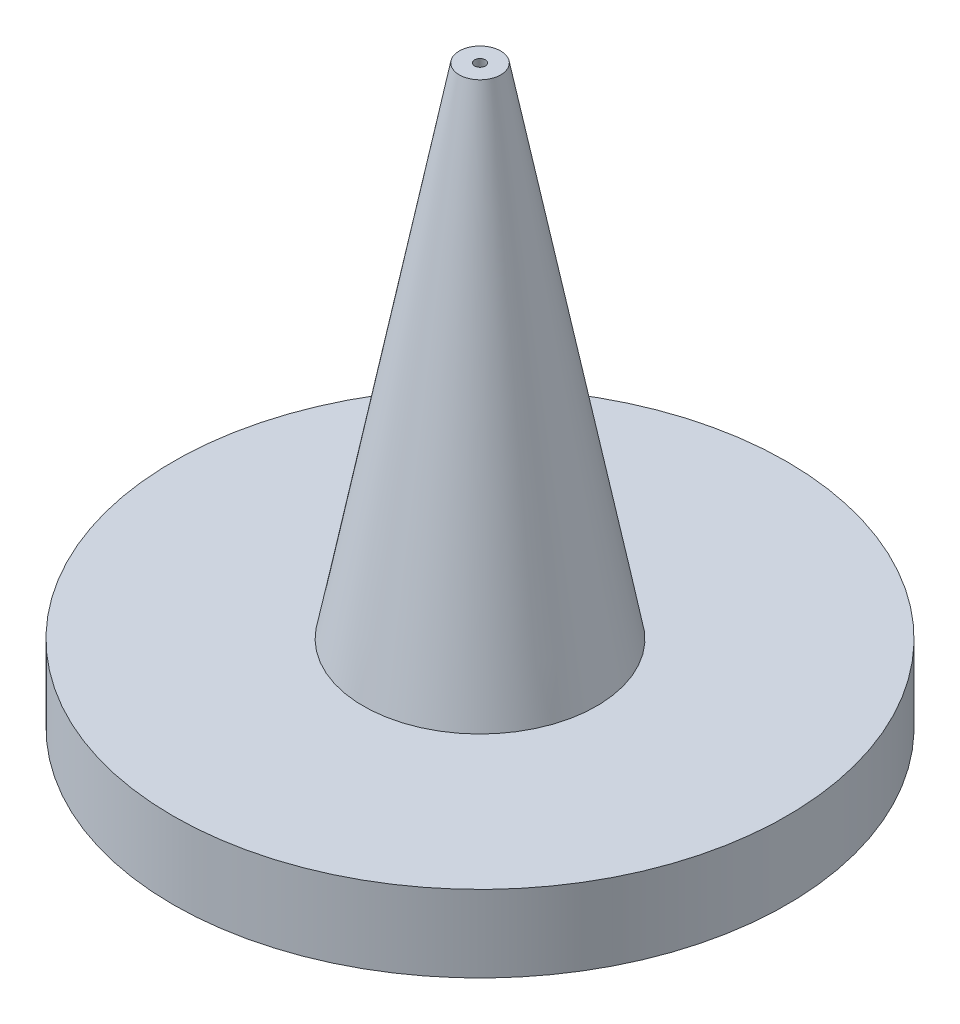
SolidWorks part; units mm, degrees
ref_plane "Front Plane" through (0, 0, 0) normal (0, 0, 1) x (1, 0, 0)
ref_plane "Top Plane" through (0, 0, 0) normal (0, 1, 0) x (1, 0, 0)
ref_plane "Right Plane" through (0, 0, 0) normal (1, 0, 0) x (0, 0, -1)
sketch "Sketch1" plane through (0, 0, 0) normal (0, 0, 1) x (1, 0, 0)
  line L0 (0, 0) -> (0, 19.05)
  line L1 (3.3528, 0) -> (10.16, 0)
  line L2 (0.1778, 19.05) -> (0.6858, 19.05)
  line L3 (10.16, 0) -> (10.16, 2.54)
  line L4 (0.6858, 19.05) -> (3.8608, 2.54)
  line L5 (3.3528, 0) -> (0.1778, 19.05)
  line L7 (10.16, 2.54) -> (3.8608, 2.54)
revolve "Revolve1" add sketch "Sketch1" angle 360 about L0
